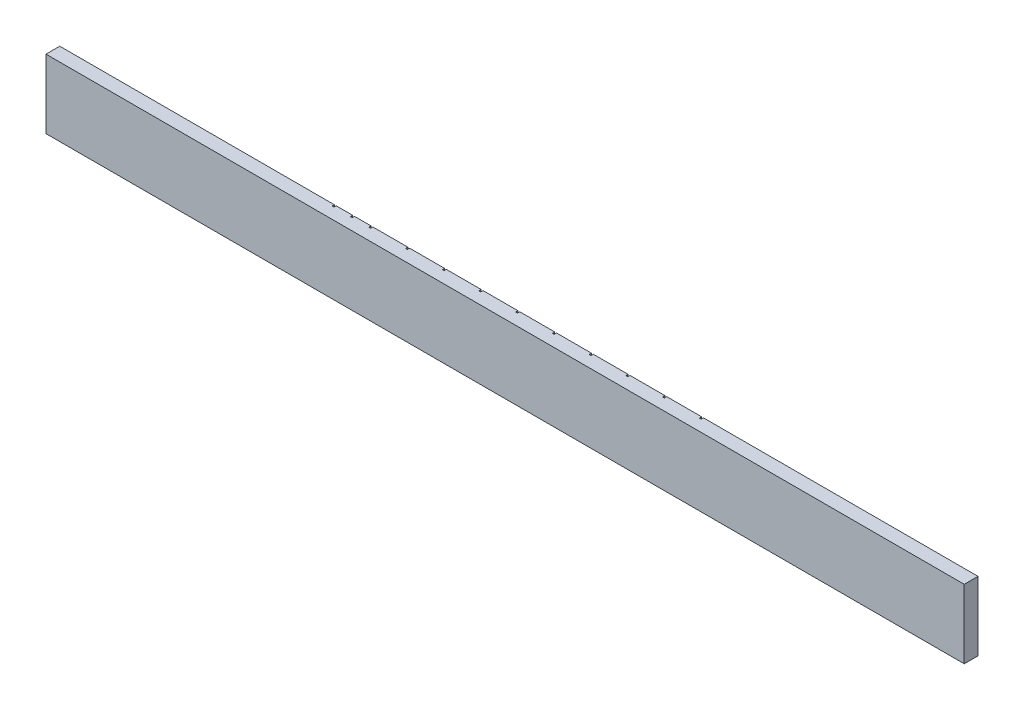
SolidWorks part; units mm, degrees
material "Brass"
ref_plane "Front Plane" through (0, 0, 0) normal (0, 0, 1) x (1, 0, 0)
ref_plane "Top Plane" through (0, 0, 0) normal (0, 1, 0) x (1, 0, 0)
ref_plane "Right Plane" through (0, 0, 0) normal (1, 0, 0) x (0, 0, -1)
sketch "Sketch1" plane through (0, 0, 0) normal (0, 0, 1) x (1, 0, 0)
  line L0 (0, 0) -> (200, 0)
  line L1 (200, 0) -> (200, 15)
  line L2 (200, 15) -> (0, 15)
  line L3 (0, 15) -> (0, 0)
  dimension "D1" = 200
  dimension "D2" = 15
extrude "Boss-Extrude1" add sketch "Sketch1" along normal blind 3
sketch "Sketch2" plane through (0, 0, 0) normal (0, 0, 1) x (1, 0, 0)
  line L0 (59.8, 9) -> (60.2, 9)
  line L1 (60.2, 9) -> (60.2, 16)
  line L2 (60.2, 16) -> (59.8, 16)
  line L3 (59.8, 16) -> (59.8, 9)
  dimension "D1" = 0.4
  dimension "D2" = 7
extrude "Cut-Extrude2" cut sketch "Sketch2" against normal blind 0.5 and the other way blind 0.5
pattern_linear "LPattern1" count 11 spacing 8 along (1, 0, 0) of "Cut-Extrude2"
sketch "Sketch3" plane through (0, 0, 0) normal (0, 0, 1) x (1, 0, 0)
  line L0 (63.8, 8) -> (64.2, 8)
  line L1 (64.2, 8) -> (64.2, 16)
  line L2 (64.2, 16) -> (63.8, 16)
  line L3 (63.8, 16) -> (63.8, 8)
  dimension "D1" = 0.4
  dimension "D2" = 8
extrude "Cut-Extrude4" cut sketch "Sketch3" against normal blind 0.5 and the other way blind 0.5
